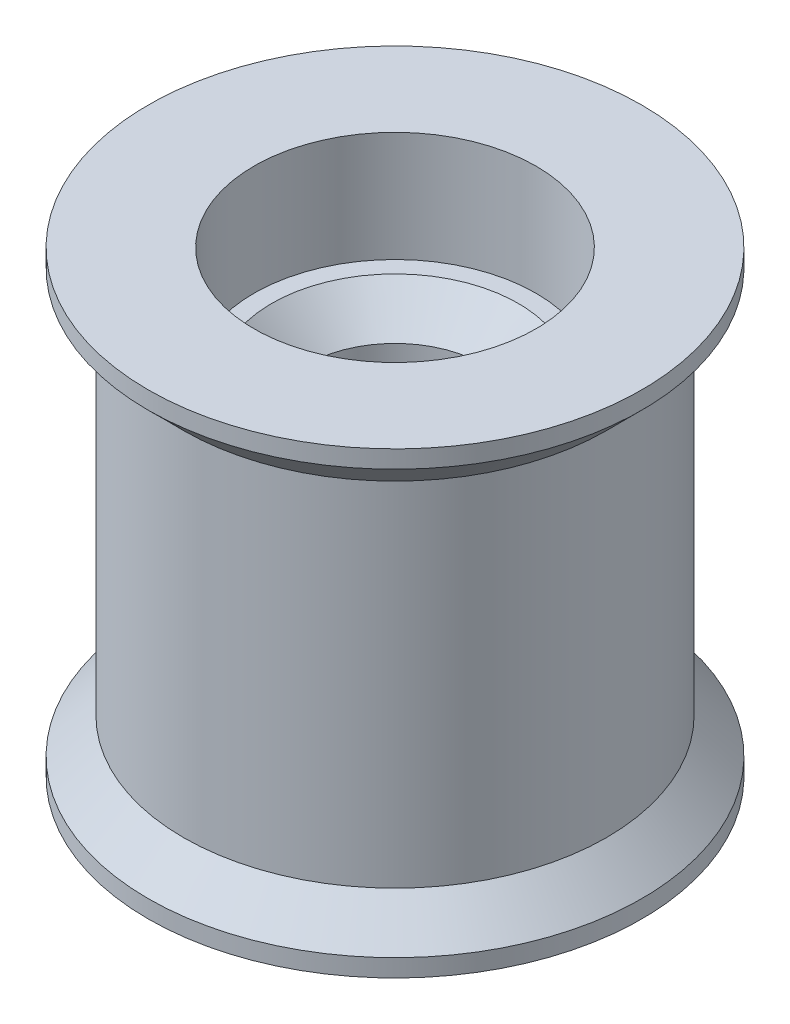
SolidWorks part; units mm, degrees
material "Markforged"
ref_plane "Front Plane" through (0, 0, 0) normal (0, 0, 1) x (1, 0, 0)
ref_plane "Top Plane" through (0, 0, 0) normal (0, 1, 0) x (1, 0, 0)
ref_plane "Right Plane" through (0, 0, 0) normal (1, 0, 0) x (0, 0, -1)
other "Bounding Box"
ref_plane "Default Plane" through (-8.9266, -12.7485, 0) normal (-0.1736, 0.9848, 0) x (0.9848, 0.1736, 0)
sketch "Sketch2" plane through (0, 0, 0) normal (1, 0, 0) x (0, 0, -1)
  line L0 (0, 0) -> (196218.8196, 0) construction
  line L1 (0, 0) -> (0, 196218.8196) construction
  line L2 (2.5, 0) -> (2.5, 3.375)
  line L3 (2.5, 3.375) -> (4, 3.375)
  line L4 (4, 3.375) -> (4, 6.5)
  line L5 (4, 6.5) -> (7, 6.5)
  line L6 (7, 6.5) -> (7, 6)
  line L7 (7, 6) -> (6, 5)
  line L8 (6, 5) -> (6, 0)
  line L9 (6, 0) -> (2.5, 0)
  dimension "D1" = 5
  dimension "D2" = 8
  dimension "D3" = 3.125
  dimension "D4" = 12
  dimension "D5" = 14
  dimension "D6" = 10
  dimension "D7" = 0.5
  dimension "D8" = 1.5
revolve "Revolve1" add sketch "Sketch2" angle 360 about L1
mirror "Mirror1" about plane through (0, 0, 0) normal (0, 1, 0) of "Revolve1"
chamfer "Chamfer1" distance 1 angle 45 2 edges at (0, -3.375, -2.5) (0, 3.375, -2.5)
